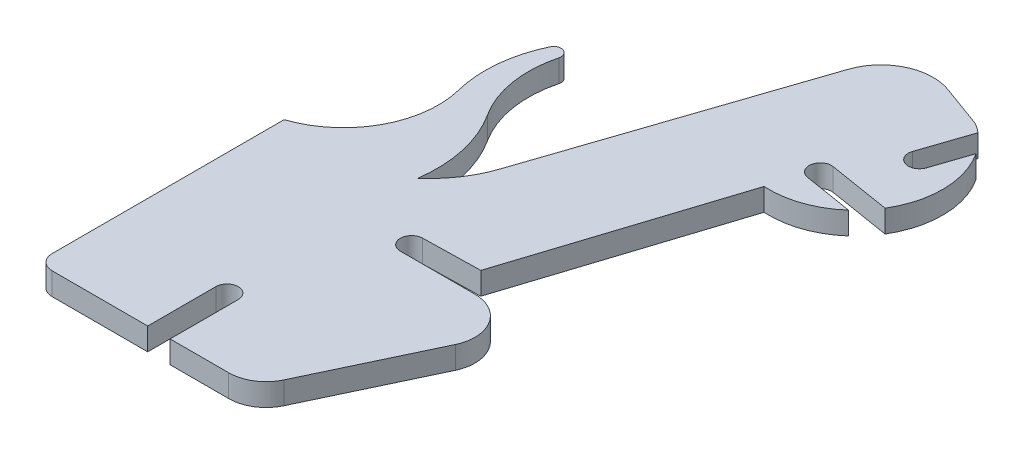
SolidWorks part; units mm, degrees
ref_plane "Front Plane" through (0, 0, 0) normal (0, 0, 1) x (1, 0, 0)
ref_plane "Top Plane" through (0, 0, 0) normal (0, 1, 0) x (1, 0, 0)
ref_plane "Right Plane" through (0, 0, 0) normal (1, 0, 0) x (0, 0, -1)
sketch "Sketch1" plane through (0, 0, 0) normal (0, 1, 0) x (1, 0, 0)
  line L0 (0, 33.06) -> (0, 0)
  line L1 (0, 0) -> (14.8, 0)
  line L2 (14.8, 0) -> (14.8, 9.13)
  line L3 (17.8, 9.13) -> (17.8, 0)
  line L4 (17.8, 0) -> (28.82, 0)
  line L5 (28.82, 0) -> (40.93, 25.6)
  line L6 (40.93, 25.6) -> (23.0399, 25.6)
  line L7 (23.008, 28.5997) -> (30.66, 28.7624)
  line L8 (30.66, 28.7624) -> (39.8931, 57.4621)
  line L9 (46.79, 78.9) -> (34.22, 83.4847)
  line L10 (34.22, 83.4847) -> (20.1714, 41.7583)
  line L11 (50.5222, 63.05) -> (42.2216, 64.4)
  line L12 (41.74, 61.4389) -> (48.2921, 60.3733)
  line L13 (47.9869, 78.0317) -> (45.7764, 71.4663)
  line L14 (48.6196, 70.509) -> (50.288, 75.4644)
  arc A0 (14.8, 9.13) -> (17.8, 9.13) centre (16.3, 9.13) cw
  arc A1 (23.0399, 25.6) -> (23.008, 28.5997) centre (23.0399, 27.1) cw
  arc A2 (20.1714, 41.7583) -> (15.7532, 35.2303) centre (6.1787, 46.4694) cw
  arc A8 (39.8931, 57.4621) -> (48.2921, 60.3733) centre (40.5731, 69.0717) ccw
  arc A9 (42.2216, 64.4) -> (41.74, 61.4389) centre (41.9808, 62.9195) ccw
  arc A10 (50.5222, 63.05) -> (50.288, 75.4644) centre (40.5731, 69.0717) ccw
  arc A11 (45.7764, 71.4663) -> (48.6196, 70.509) centre (47.198, 70.9877) ccw
  arc A12 (47.9869, 78.0317) -> (46.79, 78.9) centre (40.5731, 69.0717) ccw
  arc A13 (15.7532, 35.2303) -> (13.089, 47.2128) centre (-1.6815, 37.6413) ccw
  arc A14 (8.2591, 48.1984) -> (0, 33.06) centre (-4.0768, 45.1063) cw
  arc A15 (13.089, 47.2128) -> (11.2329, 58.6549) centre (25.1756, 55.0451) cw
  arc A16 (11.2329, 58.6549) -> (9.3614, 59.3342) centre (10.2649, 58.9056) ccw
  arc A17 (9.3614, 59.3342) -> (8.2591, 48.1984) centre (24.3397, 52.2291) ccw
  point P18 (21.54, 27.0841)
  point P21 (16.3, 10.63)
  point P38 (46.7193, 69.5661)
  dimension "D3" = 1.5
  dimension "D9" = 9.12
  dimension "D15" = 14.7645
  dimension "D22" = 1
  dimension "D23" = 8.2591
  dimension "D24" = 9.3614
  dimension "D25" = 17.6007
  dimension "D26" = 12.7175
  dimension "D27" = 14.4024
  dimension "D28" = 16.578
  dimension "D1" = 14.8
  dimension "D2" = 10.63
  dimension "D4" = 40.93
  dimension "D5" = 25.6
  dimension "11.02" = 11.02
  dimension "D6" = 30.66
  dimension "D7" = 69.0717
  dimension "D8" = 33.06
  dimension "D10" = 13.38
  dimension "D11" = 46.79
  dimension "D12" = 78.9
  dimension "D13" = 34.22
  dimension "D14" = 13.4094
  dimension "D16" = 22.52
  dimension "D17" = 14.5
  dimension "D18" = 23.94
  dimension "D19" = 15.85
  dimension "D20" = 28.6998
  dimension "D21" = 13.68
  dimension "D29" = 10.2649
  dimension "D30" = 11.2329
  dimension "D31" = 13.089
  dimension "D32" = 1.1969
  dimension "D33" = 8.56
extrude "Boss-Extrude1" add sketch "Sketch1" along normal mid plane 3
fillet "Fillet1" radius 5 1 edges at (40.93, 0, -25.6)
fillet "Fillet3" radius 7 1 edges at (34.22, 0, -83.4847)
fillet "Fillet4" radius 2 1 edges at (0, 0, 0)
fillet "Fillet5" radius 5 1 edges at (28.82, 0, 0)
sketch "Sketch2" plane through (0, 1.5, 0) normal (0, 1, 0) x (1, 0, 0)
  arc A0 (50.5222, 63.05) -> (50.288, 75.4644) centre (40.5731, 69.0717) ccw construction
  arc A1 (39.8931, 57.4621) -> (48.2921, 60.3733) centre (40.5731, 69.0717) ccw construction
  arc A2 (50.5222, 63.05) -> (50.288, 75.4644) centre (40.5731, 69.0717) ccw
  arc A3 (39.8931, 57.4621) -> (48.2921, 60.3733) centre (40.5731, 69.0717) ccw
  arc A4 (39.8931, 57.4621) -> (50.288, 75.4644) centre (32.6573, 73.6424) ccw
  arc A5 (48.2921, 60.3733) -> (50.5222, 63.05) centre (40.5731, 69.0717) ccw
  dimension "D1" = 7.9159
extrude "Cut-Extrude1" [suppressed] cut sketch "Sketch2" against normal blind 10
